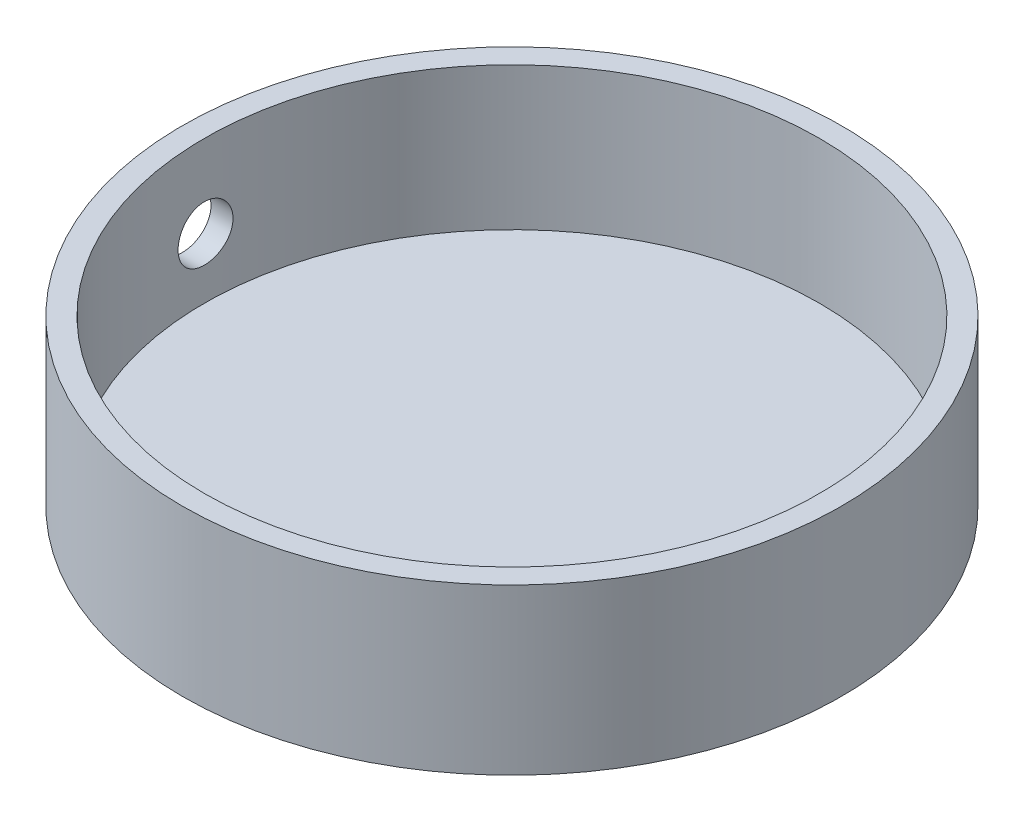
SolidWorks part; units mm, degrees
ref_plane "Front Plane" through (0, 0, 0) normal (0, 0, 1) x (1, 0, 0)
ref_plane "Top Plane" through (0, 0, 0) normal (0, 1, 0) x (1, 0, 0)
ref_plane "Right Plane" through (0, 0, 0) normal (1, 0, 0) x (0, 0, -1)
sketch "Sketch1" plane through (0, 0, 0) normal (0, 1, 0) x (1, 0, 0)
  circle A0 centre (0, 0) radius 38.1
  dimension "D1" = 76.2
extrude "Boss-Extrude1" add sketch "Sketch1" along normal blind 2.54
sketch "Sketch2" plane through (0, 2.54, 0) normal (0, 1, 0) x (1, 0, 0)
  circle A0 centre (0, 0) radius 38.1
  circle A1 centre (0, 0) radius 35.56
  circle A2 centre (0, 0) radius 38.1 construction
  dimension "D1" = 2.54
extrude "Boss-Extrude2" add sketch "Sketch2" along normal blind 16.51
ref_plane "Plane1" through (-38.1, 0, 0) normal (-1, 0, 0) x (0, 0, 1)
sketch "Sketch3" plane through (-38.1, 0, 0) normal (-1, 0, 0) x (0, 0, 1)
  line L0 (0, 19.05) -> (0, 0) construction
  line L1 (38.1, 19.05) -> (-38.1, 19.05) construction
  circle A0 centre (0, 9.525) radius 3.175
  dimension "D1" = 6.35
extrude "Cut-Extrude1" cut sketch "Sketch3" against normal up to surface (2.682 mm away)
